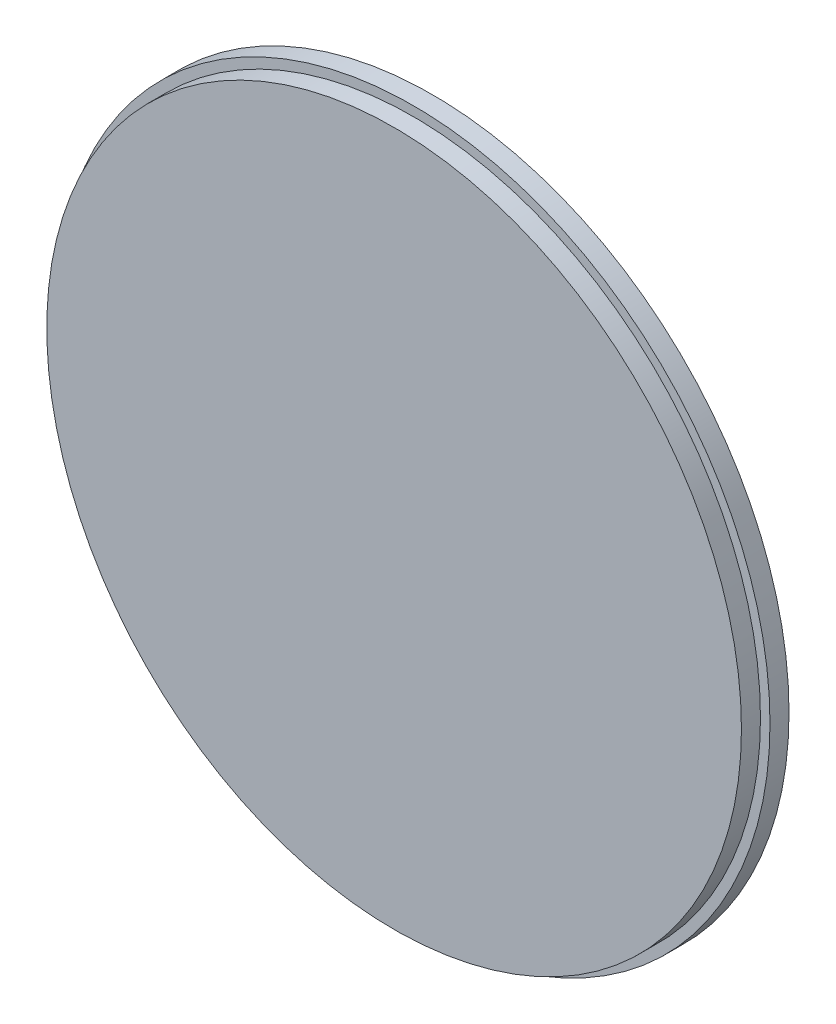
SolidWorks part; units mm, degrees
ref_plane "Front Plane" through (0, 0, 0) normal (0, 0, 1) x (1, 0, 0)
ref_plane "Top Plane" through (0, 0, 0) normal (0, 1, 0) x (1, 0, 0)
ref_plane "Right Plane" through (0, 0, 0) normal (1, 0, 0) x (0, 0, -1)
sketch "Sketch1" plane through (0, 0, 0) normal (0, 0, 1) x (1, 0, 0)
  circle A0 centre (0, 0) radius 18.75
  dimension "D1" = 37.5
extrude "Boss-Extrude1" add sketch "Sketch1" along normal blind 1
sketch "Sketch2" plane through (0, 0, 1) normal (0, 0, 1) x (1, 0, 0)
  circle A0 centre (0, 0) radius 18.25
  dimension "D1" = 36.5
extrude "Boss-Extrude2" add sketch "Sketch2" along normal blind 1
